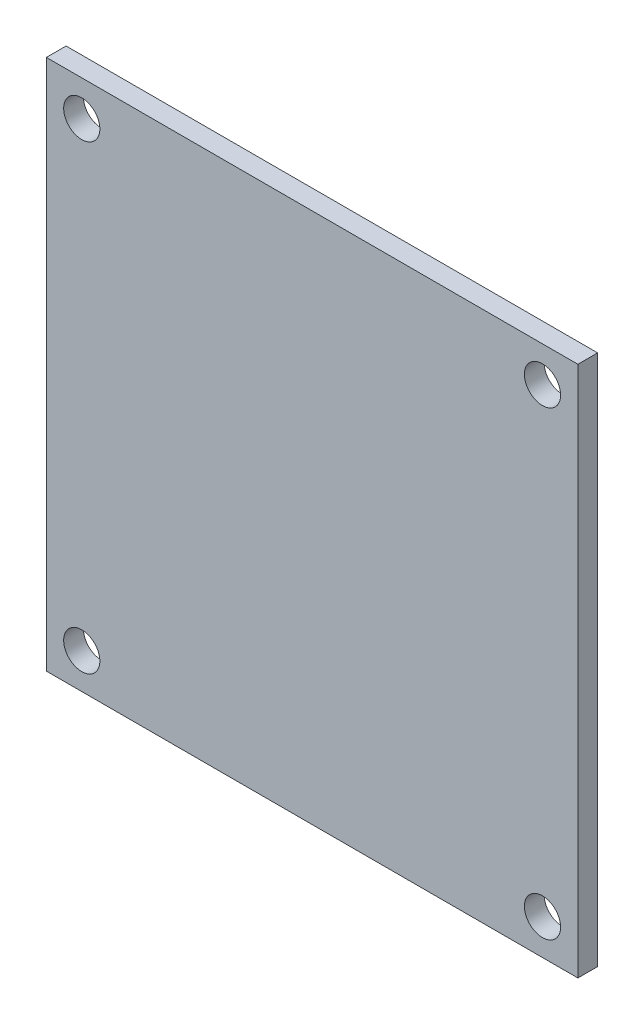
SolidWorks part; units mm, degrees
ref_plane "前视基准面" through (0, 0, 0) normal (0, 0, 1) x (1, 0, 0)
ref_plane "上视基准面" through (0, 0, 0) normal (0, 1, 0) x (1, 0, 0)
ref_plane "右视基准面" through (0, 0, 0) normal (1, 0, 0) x (0, 0, -1)
sketch "草图1" plane through (0, 0, 0) normal (0, 0, 1) x (1, 0, 0)
  line L1 (-16.15, -16.15) -> (16.15, -16.15)
  line L2 (-16.15, -16.15) -> (-16.15, 16.15)
  line L3 (-16.15, 16.15) -> (16.15, 16.15)
  line L4 (16.15, -16.15) -> (16.15, 16.15)
  line L5 (-16.15, -16.15) -> (16.15, 16.15) construction
  line L6 (-16.15, 16.15) -> (16.15, -16.15) construction
  dimension "D1" = 16.15
  dimension "D2" = 16.15
  dimension "D3" = 16.15
extrude "PCB装配包络_厚1.2" add sketch "草图1" along normal blind 1.2 from offset 16.8
sketch "草图2" plane through (0, 0, 0) normal (0, 0, 1) x (1, 0, 0)
  circle A0 centre (-14, -14) radius 1.1
  circle A1 centre (-14, 14) radius 1.1
  circle A2 centre (14, -14) radius 1.1
  circle A3 centre (14, 14) radius 1.1
  dimension "D1" = 2.2
  dimension "D2" = 14
  dimension "D3" = 14
  dimension "D4" = 14
  dimension "D5" = 14
extrude "原厂PCB孔径_非打印放孔" cut sketch "草图2" along normal blind 1.2 from offset 16.8
